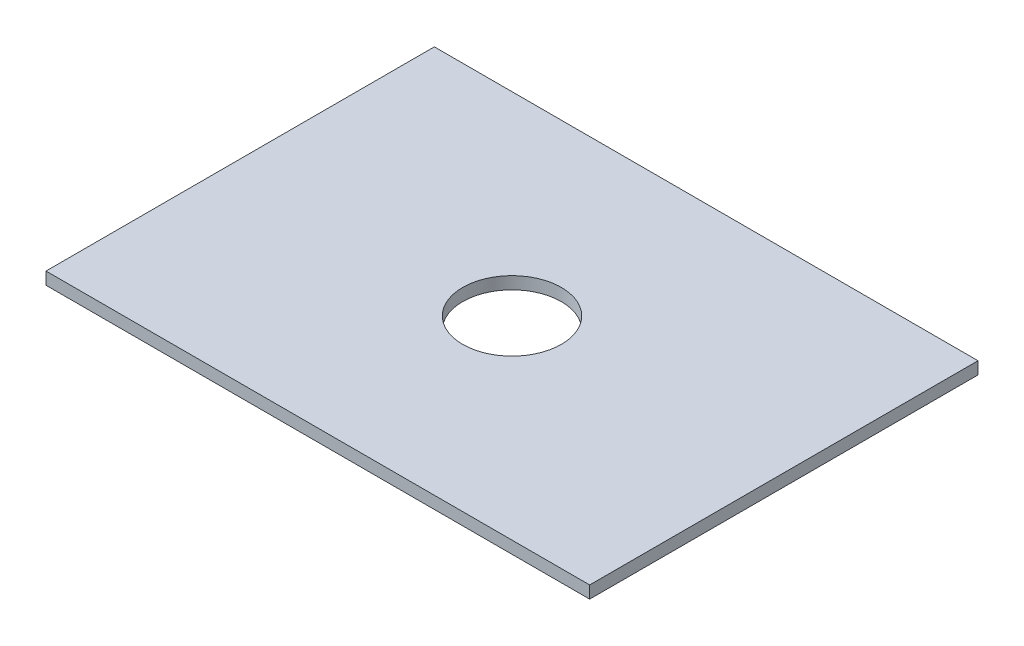
SolidWorks part; units mm, degrees
material "Oak"
ref_plane "Front Plane" through (0, 0, 0) normal (0, 0, 1) x (1, 0, 0)
ref_plane "Top Plane" through (0, 0, 0) normal (0, 1, 0) x (1, 0, 0)
ref_plane "Right Plane" through (0, 0, 0) normal (1, 0, 0) x (0, 0, -1)
sketch "Sketch1" plane through (0, 0, 0) normal (0, 1, 0) x (1, 0, 0)
  line L1 (0, 0) -> (140, 0)
  line L2 (0, 0) -> (0, 100)
  line L3 (0, 100) -> (140, 100)
  line L4 (140, 0) -> (140, 100)
  dimension "D1" = 140
  dimension "D2" = 100
extrude "Boss-Extrude1" add sketch "Sketch1" along normal blind 3.175
sketch "Sketch2" plane through (0, 3.175, 0) normal (0, 1, 0) x (1, 0, 0)
  line L0 (70, 100) -> (70, 0) construction
  line L1 (140, 100) -> (0, 100) construction
  line L2 (0, 0) -> (140, 0) construction
  line L3 (0, 50) -> (140, 50) construction
  line L4 (0, 100) -> (0, 0) construction
  line L5 (140, 0) -> (140, 100) construction
  circle A0 centre (70, 50) radius 12.705
  dimension "D1" = 25.41
extrude "Cut-Extrude1" cut sketch "Sketch2" against normal blind 10
